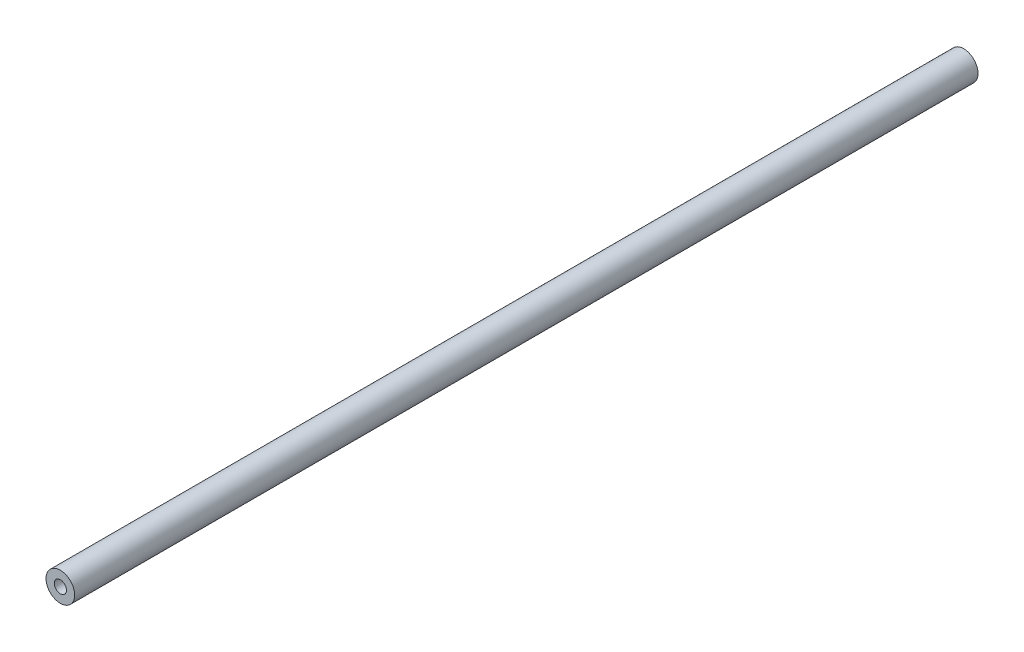
SolidWorks part; units mm, degrees
ref_plane "Front Plane" through (0, 0, 0) normal (0, 0, 1) x (1, 0, 0)
ref_plane "Top Plane" through (0, 0, 0) normal (0, 1, 0) x (1, 0, 0)
ref_plane "Right Plane" through (0, 0, 0) normal (1, 0, 0) x (0, 0, -1)
sketch "Sketch1" plane through (0, 0, 0) normal (0, 0, 1) x (1, 0, 0)
  circle A1 centre (0, 0) radius 4.7625
  dimension "D1" = 9.525
extrude "Boss-Extrude1" add sketch "Sketch1" along normal mid plane 300.0375
hole_wizard "#10-32 Tapped Hole1" positions "3DSketch1" profile "Sketch3" tap size "#10-32" standard "ANSI Inch"
sketch3d "3DSketch1"
  line L0 (0, 0, 150.0188) -> (0, 0, -150.0188) construction
  point P0 (0, 0, 150.0188)
  point P5 (0, 0, -150.0188)
sketch "Sketch3" plane through (0, 0, 150.0188) normal (1, 0, 0) x (0, -1, 0)
  line L0 (0, 0) -> (0, 13.1513)
  line L1 (0, 13.1513) -> (2.0193, 11.938)
  line L2 (2.0193, 11.938) -> (2.0193, 0)
  line L5 (2.0193, 0) -> (0, 0)
  line L10 (0, 13.1513) -> (-2.0193, 11.938) construction
  line L11 (0, -6.35) -> (0, 107.95) construction
  dimension "Tap Drill Dia." = 4.0386
  dimension "Tap Drill Depth" = 11.938
  dimension "Drill Angle" = 118
cosmetic thread "Hole Thread1" parameters "D1"=9.652, "D2"=4.826
cosmetic thread "Hole Thread2" parameters "D1"=9.652, "D2"=4.826
